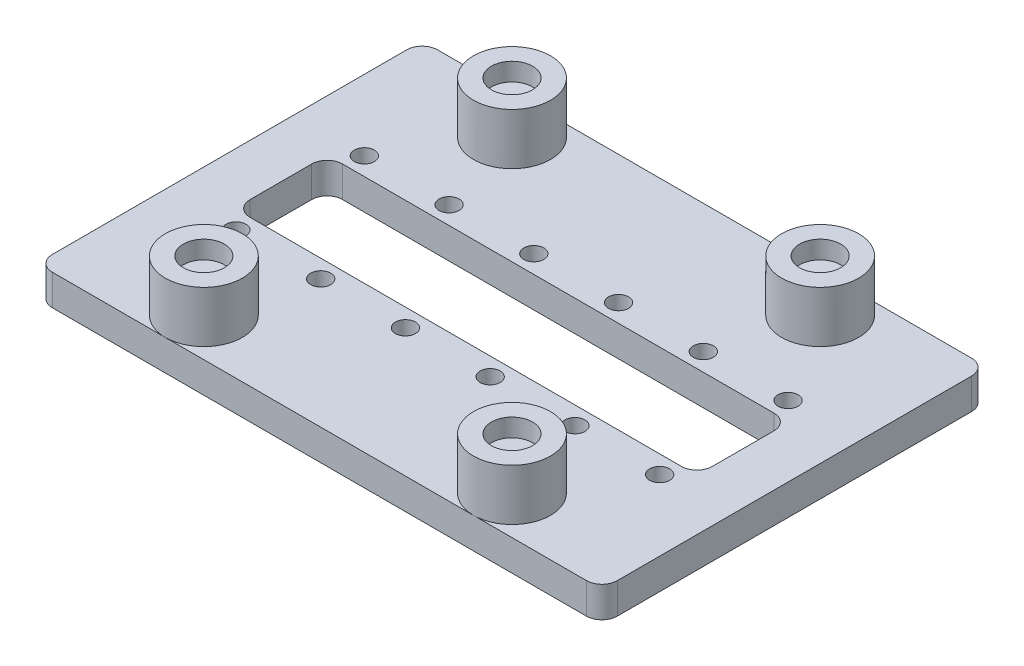
SolidWorks part; units mm, degrees
ref_plane "Front Plane" through (0, 0, 0) normal (0, 0, 1) x (1, 0, 0)
ref_plane "Top Plane" through (0, 0, 0) normal (0, 1, 0) x (1, 0, 0)
ref_plane "Right Plane" through (0, 0, 0) normal (1, 0, 0) x (0, 0, -1)
sketch "Sketch1" plane through (0, 0, 0) normal (0, 1, 0) x (1, 0, 0)
  line L1 (-55, 37.5) -> (55, 37.5)
  line L2 (-55, 37.5) -> (-55, -37.5)
  line L3 (-55, -37.5) -> (55, -37.5)
  line L4 (55, 37.5) -> (55, -37.5)
  line L5 (-55, 37.5) -> (55, -37.5) construction
  line L6 (-55, -37.5) -> (55, 37.5) construction
  point P0 (0, 0)
  dimension "D1" = 110
  dimension "D2" = 75
extrude "Boss-Extrude1" add sketch "Sketch1" along normal blind 6
sketch "Sketch2" plane through (0, 6, 0) normal (0, 1, 0) x (1, 0, 0)
  line L1 (-45, 9) -> (45, 9)
  line L2 (-45, 9) -> (-45, -9)
  line L3 (-45, -9) -> (45, -9)
  line L4 (45, 9) -> (45, -9)
  line L5 (-45, 9) -> (45, -9) construction
  line L6 (-45, -9) -> (45, 9) construction
  point P0 (0, 0)
  dimension "D1" = 90
  dimension "D2" = 18
extrude "Cut-Extrude1" cut sketch "Sketch2" against normal blind 10
fillet "Fillet1" radius 3 4 edges at (45, 3, -9) (45, 3, 9) (-45, 3, -9) (-45, 3, 9)
hole_wizard "Ø3.9 (3.9) Diameter Hole1" positions "Sketch4" profile "Sketch5" hole size "Ø3.9" standard "ISO"
sketch "Sketch4" plane through (0, 0, 0) normal (0, -1, 0) x (-1, 0, 0)
  line L1 (-8.25, 12.5) -> (8.25, 12.5)
  line L2 (-8.25, 12.5) -> (-8.25, -12.5)
  line L3 (-8.25, -12.5) -> (8.25, -12.5)
  line L4 (8.25, 12.5) -> (8.25, -12.5)
  line L5 (-8.25, 12.5) -> (8.25, -12.5) construction
  line L6 (-8.25, -12.5) -> (8.25, 12.5) construction
  line L7 (8.25, -12.5) -> (24.75, -12.5) construction
  line L8 (24.75, -12.5) -> (41.25, -12.5) construction
  line L9 (8.25, 12.5) -> (24.75, 12.5) construction
  line L10 (24.75, 12.5) -> (41.25, 12.5) construction
  line L12 (-8.25, 12.5) -> (-24.75, 12.5) construction
  line L13 (-24.75, 12.5) -> (-41.25, 12.5) construction
  line L15 (-8.25, -12.5) -> (-24.75, -12.5) construction
  line L16 (-24.75, -12.5) -> (-41.25, -12.5) construction
  line L17 (41.25, 12.5) -> (41.25, -12.5) construction
  line L19 (24.75, 12.5) -> (24.75, -12.5) construction
  line L21 (-24.75, 12.5) -> (-24.75, -12.5) construction
  line L23 (-41.25, 12.5) -> (-41.25, -12.5) construction
  point P1 (0, 0)
  point P2 (8.25, -12.5)
  point P51 (-8.25, 12.5)
  point P52 (-8.25, -12.5)
  point P53 (8.25, 12.5)
  point P58 (24.75, -12.5)
  point P60 (41.25, -12.5)
  point P76 (24.75, 12.5)
  point P78 (41.25, 12.5)
  point P81 (-24.75, 12.5)
  point P83 (-41.25, 12.5)
  point P86 (-24.75, -12.5)
  point P88 (-41.25, -12.5)
  dimension "D1" = 16.5
  dimension "D2" = 25
sketch "Sketch5" plane through (0, 0, 0) normal (1, 0, 0) x (0, 0, -1)
  line L0 (0, 0) -> (0, 16.1717)
  line L1 (0, 16.1717) -> (1.95, 15)
  line L2 (1.95, 15) -> (1.95, 0.025)
  line L3 (1.95, 0.025) -> (1.975, 0)
  line L5 (1.975, 0) -> (0, 0)
  line L6 (-1.95, 0.025) -> (-1.975, 0) construction
  line L10 (0, 16.1717) -> (-1.95, 15) construction
  line L11 (0, -6.35) -> (0, 107.95) construction
  dimension "Hole Dia." = 3.9
  dimension "Hole Depth" = 15
  dimension "Near C'Sink Dia." = 3.95
  dimension "Near C'Sink Angle" = 90
  dimension "Drill Angle" = 118
fillet "Fillet2" radius 3 4 edges at (55, 3, -37.5) (-55, 3, -37.5) (-55, 3, 37.5) (55, 3, 37.5)
sketch "Sketch6" plane through (0, 6, 0) normal (0, 1, 0) x (1, 0, 0)
  line L1 (-30, 30) -> (30, 30) construction
  line L2 (-30, 30) -> (-30, -30) construction
  line L3 (-30, -30) -> (30, -30) construction
  line L4 (30, 30) -> (30, -30) construction
  line L5 (-30, 30) -> (30, -30) construction
  line L6 (-30, -30) -> (30, 30) construction
  circle A0 centre (-30, -30) radius 7.5
  circle A1 centre (30, -30) radius 7.5
  circle A2 centre (30, 30) radius 7.5
  circle A3 centre (-30, 30) radius 7.5
  point P0 (0, 0)
  dimension "D3" = 15
  dimension "D1" = 60
  dimension "D2" = 60
extrude "Boss-Extrude3" add sketch "Sketch6" along normal blind 10
sketch "Sketch7" plane through (0, 16, 0) normal (0, 1, 0) x (1, 0, 0)
  circle A0 centre (-30, 30) radius 4
  circle A1 centre (30, 30) radius 4
  circle A2 centre (30, -30) radius 4
  circle A3 centre (-30, -30) radius 4
  dimension "D1" = 8
extrude "Cut-Extrude2" cut sketch "Sketch7" against normal blind 3.5
